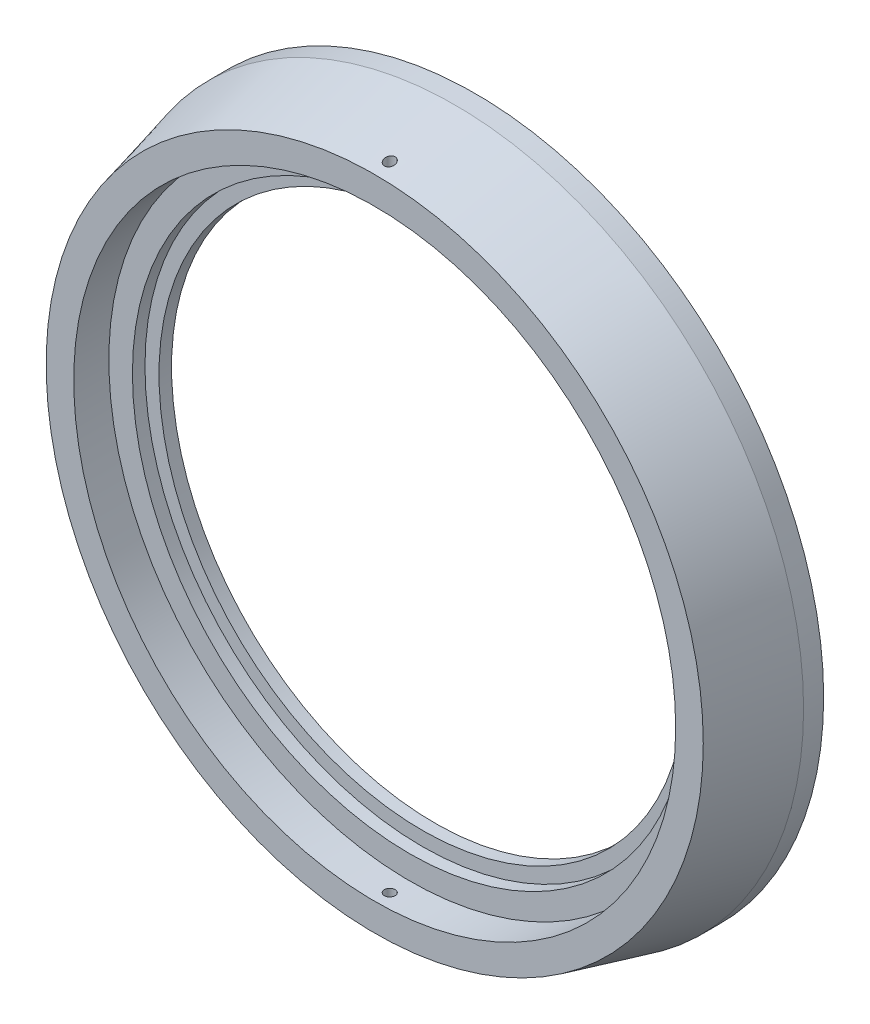
SolidWorks part; units mm, degrees
ref_plane "Front Plane" through (0, 0, 0) normal (0, 0, 1) x (1, 0, 0)
ref_plane "Top Plane" through (0, 0, 0) normal (0, 1, 0) x (1, 0, 0)
ref_plane "Right Plane" through (0, 0, 0) normal (1, 0, 0) x (0, 0, -1)
sketch "Sketch1" plane through (0, 0, 0) normal (0, 0, 1) x (1, 0, 0)
  circle A0 centre (0, 0) radius 88.265
  dimension "D1" = 176.53
extrude "Boss-Extrude1" add sketch "Sketch1" along normal blind 25.4
sketch "Sketch2" plane through (0, 0, 25.4) normal (0, 0, 1) x (1, 0, 0)
  circle A0 centre (0, 0) radius 76.2
  dimension "D1" = 152.4
extrude "Cut-Extrude1" cut sketch "Sketch2" against normal blind 8.89
sketch "Sketch3" plane through (0, 0, 16.51) normal (0, 0, 1) x (1, 0, 0)
  circle A0 centre (0, 0) radius 70.231
  dimension "D1" = 140.462
extrude "Cut-Extrude2" cut sketch "Sketch3" against normal blind 3.175
sketch "Sketch4" plane through (0, 0, 13.335) normal (0, 0, 1) x (1, 0, 0)
  circle A0 centre (0, 0) radius 66.675
  dimension "D1" = 133.35
extrude "Cut-Extrude3" cut sketch "Sketch4" against normal through all
chamfer "Chamfer1" distance 10.16 distance2 18.415 1 edges at (66.675, 0, 0)
chamfer "Chamfer2" distance 20.32 distance2 5.08 1 edges at (88.265, 0, 25.4)
sketch "Sketch5" plane through (0, 0, 0) normal (0, 1, 0) x (1, 0, 0)
  line L0 (-83.185, -25.4) -> (83.185, -25.4) construction
  circle A0 centre (0, -21.59) radius 1.3525
  dimension "D1" = 2.7051
  dimension "D2" = 3.81
extrude "Cut-Extrude4" cut sketch "Sketch5" against normal through all both and the other way through all
